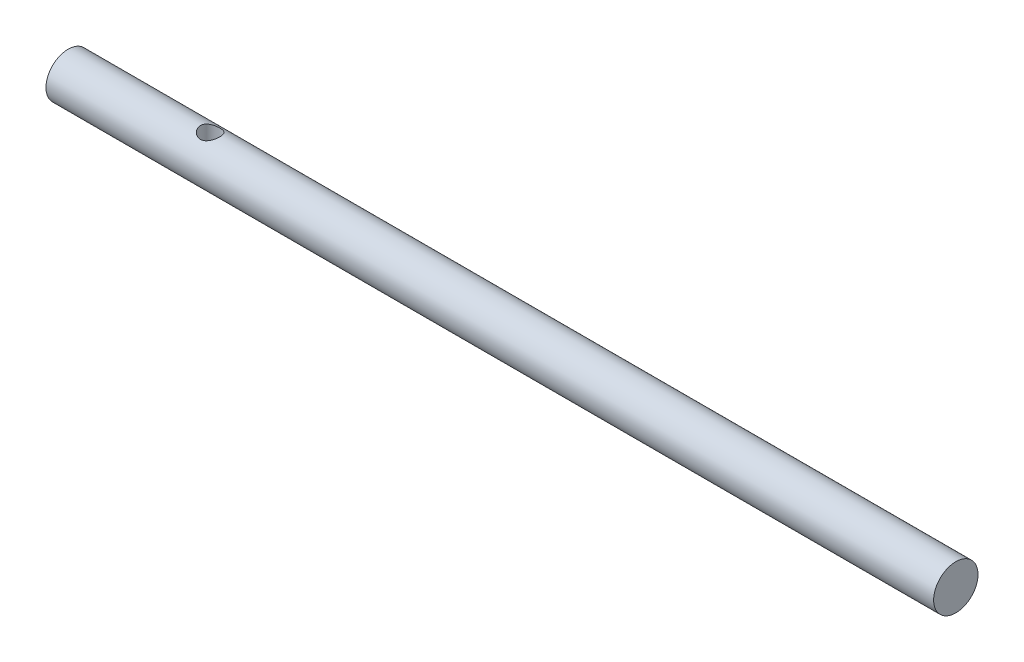
SolidWorks part; units mm, degrees
ref_plane "Front Plane" through (0, 0, 0) normal (0, 0, 1) x (1, 0, 0)
ref_plane "Top Plane" through (0, 0, 0) normal (0, 1, 0) x (1, 0, 0)
ref_plane "Right Plane" through (0, 0, 0) normal (1, 0, 0) x (0, 0, -1)
sketch "Sketch3" plane through (0, 0, 0) normal (1, 0, 0) x (0, 0, -1)
  circle A0 centre (0, 0) radius 2.5
  dimension "D1" = 5
extrude "Boss-Extrude1" add sketch "Sketch3" along normal mid plane 100
ref_plane "Plane1" through (0, 2.5, 0) normal (0, 1, 0) x (1, 0, 0)
sketch "Sketch4" plane through (0, 2.5, 0) normal (0, 1, 0) x (1, 0, 0)
  line L0 (-50, 2.5) -> (-50, -2.5) construction
  line L1 (-50, 2.5) -> (-50, -2.5)
  line L2 (-34, 2.5) -> (-34, -2.5) construction
  line L3 (50, 2.5) -> (-50, 2.5) construction
  line L4 (-50, -2.5) -> (50, -2.5) construction
  circle A0 centre (-34, 0) radius 1.1
  dimension "D2" = 2.2
  dimension "D1" = 16
extrude "Cut-Extrude1" cut sketch "Sketch4" against normal up to next contours A0
